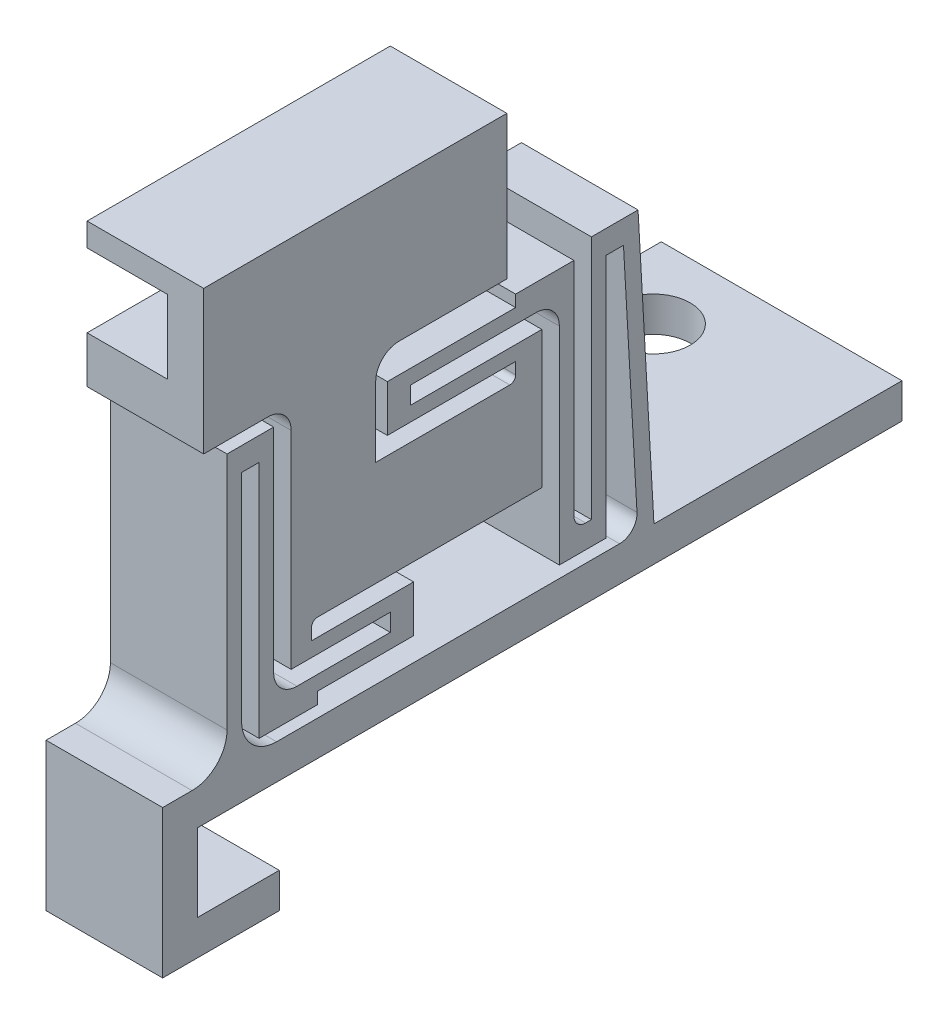
SolidWorks part; units mm, degrees
ref_plane "Front Plane" through (0, 0, 0) normal (0, 0, 1) x (1, 0, 0)
ref_plane "Top Plane" through (0, 0, 0) normal (0, 1, 0) x (1, 0, 0)
ref_plane "Right Plane" through (0, 0, 0) normal (1, 0, 0) x (0, 0, -1)
sketch "Sketch1" plane through (0, 0, 0) normal (1, 0, 0) x (0, 0, -1)
  line L0 (3.7437, -1.0669) -> (8.3687, -1.0669)
  line L1 (-4.6313, -1.0669) -> (-1.8813, -1.0669)
  line L2 (-4.6313, -1.0669) -> (-4.6313, 5.0831)
  line L3 (-4.6313, 5.0831) -> (8.3687, 5.0831)
  line L4 (8.3687, -1.0669) -> (8.3687, 5.0831)
  line L6 (-0.8813, -2.0669) -> (-0.8813, -10.9419)
  line L8 (2.7437, -2.0669) -> (2.7437, -5.0669)
  line L13 (0.2437, -9.5669) -> (9.8687, -9.5669)
  line L14 (8.7437, -4.8169) -> (8.7437, -4.3169)
  line L16 (9.8687, -9.5669) -> (9.8687, -3.6919)
  line L17 (3.2437, -2.3169) -> (3.2437, -4.3169)
  line L20 (8.7437, -4.3169) -> (3.2437, -4.3169)
  line L25 (4.2437, -3.6919) -> (4.2437, -2.9419)
  line L26 (3.2437, -2.3169) -> (8.7437, -2.3169)
  line L28 (4.2437, -2.9419) -> (9.6187, -2.9419)
  line L32 (8.7437, -2.3169) -> (8.7437, -1.8169)
  line L33 (8.7437, -1.8169) -> (11.2437, -1.8169)
  line L35 (-0.8813, -10.9419) -> (3.3687, -10.9419)
  line L36 (3.3687, -10.9419) -> (3.3687, -11.6919)
  line L37 (3.3687, -11.6919) -> (-0.6313, -11.6919)
  line L40 (-2.2563, -12.8169) -> (0.2437, -12.8169)
  line L41 (0.2437, -12.8169) -> (0.2437, -12.3169)
  line L42 (0.2437, -12.3169) -> (4.3687, -12.3169)
  line L43 (4.3687, -12.3169) -> (4.3687, -10.3169)
  line L44 (4.3687, -10.3169) -> (-0.0063, -10.3169)
  line L45 (-0.0063, -10.3169) -> (-0.0063, -9.8169)
  line L48 (-1.6313, -10.6919) -> (-1.6313, -1.5669)
  line L50 (-2.2563, -12.8169) -> (-2.2563, -2.5669)
  line L51 (-1.6313, -1.5669) -> (-3.6313, -1.5669)
  line L53 (-2.2563, -2.5669) -> (-3.0063, -2.5669)
  line L56 (10.6187, -3.9419) -> (10.6187, -12.8169)
  line L58 (11.2437, -1.8169) -> (11.2437, -11.3169)
  line L59 (10.6187, -12.8169) -> (12.6187, -12.8169)
  line L61 (11.2437, -11.8169) -> (11.9937, -11.8169) construction
  line L65 (12.6187, -12.8169) -> (12.6187, -2.3169)
  line L67 (11.9937, -11.8169) -> (11.9937, -1.3169)
  line L69 (-3.6313, -1.5669) -> (-3.6313, -11.8169)
  line L71 (-3.0063, -2.5669) -> (-3.0063, -11.8169)
  line L72 (-4.1313, -13.3169) -> (-5.1313, -13.3169) construction
  line L76 (12.6187, -2.3169) -> (13.3687, -2.3169)
  line L78 (11.9937, -1.3169) -> (13.9937, -1.3169)
  line L80 (-4.6313, -14.8169) -> (14.6755, -14.8169)
  line L82 (13.1998, -13.3169) -> (-1.5063, -13.3169)
  line L84 (4.2437, -3.6919) -> (9.8687, -3.6919)
  line L94 (8.4937, -5.0669) -> (2.7437, -5.0669)
  line L95 (13.3687, -2.3169) -> (13.9486, -12.5244)
  line L96 (4.2437, -2.3169) -> (4.2437, -2.9419) construction
  line L97 (4.2437, -3.6919) -> (4.2437, -4.3169) construction
  line L98 (3.3687, -10.3169) -> (3.3687, -10.9419) construction
  line L99 (3.3687, -11.6919) -> (3.3687, -12.3169) construction
  line L100 (8.7437, -4.3169) -> (8.7437, -5.0669) construction
  line L101 (-0.0063, -9.5669) -> (-0.0063, -10.3169)
  line L102 (13.9937, -1.3169) -> (14.6755, -13.3169)
  line L103 (11.9937, -11.8169) -> (11.7437, -11.8169)
  line L104 (-2.6313, -1.5669) -> (-2.6313, -2.5669) construction
  line L105 (14.6755, -13.3169) -> (14.6755, -14.8169)
  line L106 (-3.0063, -2.5669) -> (-3.6313, -2.5669) construction
  line L107 (-2.2563, -2.5669) -> (-1.6313, -2.5669) construction
  line L108 (-2.6313, -1.0669) -> (-2.6313, -1.5669) construction
  line L109 (3.2437, -3.3169) -> (2.7437, -3.3169) construction
  line L110 (4.3687, -12.3169) -> (4.3687, -13.3169) construction
  line L111 (-4.6313, -14.8169) -> (-4.8913, -14.8169)
  line L112 (-4.8913, -14.8169) -> (-4.8913, -18.1469)
  line L113 (-4.8913, -18.1469) -> (-1.3913, -18.1469)
  line L114 (-1.3913, -18.1469) -> (-1.3913, -19.6469)
  line L115 (-1.3913, -19.6469) -> (-6.3913, -19.6469)
  line L116 (-6.3913, -19.6469) -> (-6.3913, -13.3169)
  line L117 (-6.3913, -13.3169) -> (-5.1313, -13.3169)
  arc A0 (3.7437, -1.0669) -> (2.7437, -2.0669) centre (3.7437, -2.0669) ccw
  arc A1 (-1.8813, -1.0669) -> (-0.8813, -2.0669) centre (-1.8813, -2.0669) cw
  arc A2 (9.6187, -2.9419) -> (10.6187, -3.9419) centre (9.6187, -3.9419) cw
  arc A3 (-0.6313, -11.6919) -> (-1.6313, -10.6919) centre (-0.6313, -10.6919) cw
  arc A4 (-0.0063, -9.8169) -> (0.2437, -9.5669) centre (0.2437, -9.8169) cw
  arc A5 (8.7437, -4.8169) -> (8.4937, -5.0669) centre (8.4937, -4.8169) cw
  arc A6 (-1.5063, -13.3169) -> (-3.0063, -11.8169) centre (-1.5063, -11.8169) cw
  arc A7 (11.2437, -11.3169) -> (11.7437, -11.8169) centre (11.7437, -11.3169) ccw
  arc A10 (-5.1313, -13.3169) -> (-3.6313, -11.8169) centre (-5.1313, -11.8169) ccw
  arc A11 (13.9486, -12.5244) -> (13.1998, -13.3169) centre (13.1998, -12.5669) cw
  point P27 (13.9937, -13.3169)
  dimension "D4" = 1
  dimension "D14" = 0.25
  dimension "D18" = 1.5
  dimension "D20" = 0.5
  dimension "D21" = 0.75
  dimension "D2" = 13
  dimension "D3" = 6.15
  dimension "D5" = 13.75
  dimension "D6" = 19.9
  dimension "D13" = 1.5
  dimension "D25" = 5.5
  dimension "D27" = 2
  dimension "D32" = 10.75
  dimension "D33" = 0.875
  dimension "D37" = 0.5
  dimension "D39" = 2.5
  dimension "D41" = 4.125
  dimension "D42" = 1
  dimension "D11" = 0.75
  dimension "D17" = 1
  dimension "D12" = 1.25
  dimension "D15" = 11.75
  dimension "D16" = 1
  dimension "D22" = 0.75
  dimension "D7" = 11.5
  dimension "D8" = 2
  dimension "D9" = 2
  dimension "D10" = 0.6807
  dimension "D19" = 93.252
  dimension "D23" = 1
  dimension "D24" = 19.3068
  dimension "D26" = 3.33
  dimension "D28" = 1.5
  dimension "D29" = 1.5
  dimension "D30" = 5
extrude "Flexure Boss" add sketch "Sketch1" along normal blind 5
sketch "Sketch2" plane through (0, -14.8169, 0) normal (0, -1, 0) x (1, 0, 0)
  line L0 (0, 4.8913) -> (0, -14.6755) construction
  line L4 (-5.32, -7.3096) -> (-5.32, -25.3096)
  line L6 (5, 4.8913) -> (5, -14.6755) construction
  line L7 (-5.32, -25.3096) -> (5, -25.3096)
  line L12 (-5.32, -7.3096) -> (5, -7.3096)
  line L13 (5, -7.3096) -> (5, -25.3096)
  line L14 (5, 6.3913) -> (0, 6.3913) construction
  circle A0 centre (-2.435, -10.0887) radius 1.575
  circle A1 centre (-2.435, -22.0887) radius 1.575
  dimension "D1" = 16.48
  dimension "D2" = 5.32
  dimension "D3" = 12
  dimension "D4" = 3.15
  dimension "D5" = 2.435
  dimension "D6" = 18
  dimension "D8" = 7.3096
extrude "Mounting Plate Boss" add sketch "Sketch2" against normal blind 1.5
sketch "Sketch7" plane through (0, 0, 0) normal (-1, 0, 0) x (0, 0, 1)
  line L0 (-8.3687, 0.9331) -> (4.6313, 0.9331)
  line L1 (4.6313, 4.0831) -> (4.6313, 0.9331)
  line L4 (4.6313, 4.0831) -> (-1.8687, 3.0831)
  line L5 (-1.8687, 3.0831) -> (-8.3687, 4.0831)
  line L6 (-8.3687, 4.0831) -> (-8.3687, 0.9331)
  line L7 (4.6313, -1.0669) -> (4.6313, 5.0831) construction
  line L8 (-8.3687, -1.0669) -> (-8.3687, 5.0831) construction
  point P10 (-1.8687, 0.9331)
  dimension "D1" = 2
  dimension "D2" = 2.15
  dimension "D3" = 1
extrude "Dovetail Connection Cut" cut sketch "Sketch7" against normal blind 3.455
mirror "Mirror2" [suppressed]
delete or keep bodies "Body-Delete/Keep 1" [suppressed] type delete bodies bodies 108
equation "\"FlexureExtrusionThickness\"=5"
equation "\"D1@Flexure Boss\"=\"FlexureExtrusionThickness\""
equation "\"MountingHoleEdgeDist\"= 3.57mm"
equation "\"FlexureGapDist\"= .75mm"
equation "\"D11@Sketch1\"=\"FlexureGapDist\""
equation "\"FlexureCornerThicknessOffset\"= .5mm"
equation "\"D37@Sketch1\"=\"FlexureCornerThicknessOffset\""
equation "\"FlexureCornerThicknessWidth\"= 2.5mm"
equation "\"D39@Sketch1\"=\"FlexureCornerThicknessWidth\""
equation "\"FlexureConnectorWidth\"= 2mm"
equation "\"FlexureConnectorThickness\"= 1mm"
equation "\"D17@Sketch1\"=\"FlexureConnectorThickness\""
equation "\"DribblerPlateHeightFromBase\"= 13.75mm"
equation "\"D5@Sketch1\"=\"DribblerPlateHeightFromBase\""
equation "\"FlexureOverallHeight\"= 13.5mm"
equation "\"D15@Sketch1\"=\"DribblerPlateHeightFromBase\" - \"FlexureBaseHeight\" - \"FlexureClearanceGapDist\""
equation "\"FlexureBaseHeight\"= 1.5mm"
equation "\"D13@Sketch1\"=\"FlexureBaseHeight\""
equation "\"FlexureClearanceGapDist\"= .5mm"
equation "\"D23@Sketch1\"=\"FlexureConnectorThickness\""
